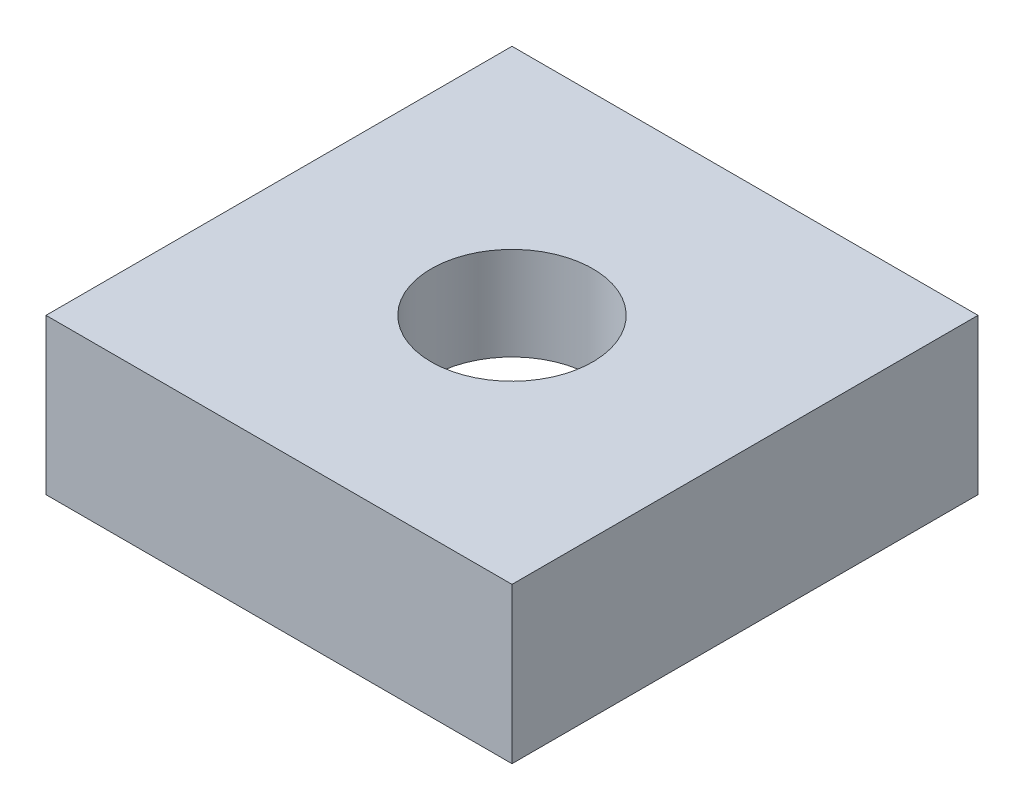
SolidWorks part; units mm, degrees
ref_plane "Alzado" through (0, 0, 0) normal (0, 0, 1) x (1, 0, 0)
ref_plane "Planta" through (0, 0, 0) normal (0, 1, 0) x (1, 0, 0)
ref_plane "Vista lateral" through (0, 0, 0) normal (1, 0, 0) x (0, 0, -1)
sketch "Croquis1" plane through (0, 0, 0) normal (0, 1, 0) x (1, 0, 0)
  line L1 (0, 0) -> (15, 0)
  line L2 (0, 0) -> (0, 15)
  line L3 (0, 15) -> (15, 15)
  line L4 (15, 0) -> (15, 15)
  dimension "D1" = 15
extrude "Saliente-Extruir1" add sketch "Croquis1" along normal blind 5
sketch "Croquis2" plane through (0, 5, 0) normal (0, 1, 0) x (1, 0, 0)
  line L0 (0, 0) -> (15, 15) construction
  circle A0 centre (7.5, 7.5) radius 2.6
  dimension "D1" = 5.2
extrude "Cortar-Extruir1" cut sketch "Croquis2" against normal blind 5
sketch "Croquis3" plane through (0, 0, 0) normal (0, -1, 0) x (1, 0, 0)
  line L1 (0, -15) -> (12.5, -15)
  line L2 (0, -15) -> (0, -2.5)
  line L3 (0, -2.5) -> (12.5, -2.5)
  line L4 (12.5, -15) -> (12.5, -2.5)
  circle A0 centre (7.5, -7.5) radius 2.6 construction
  dimension "D1" = 5
extrude "Cortar-Extruir2" cut sketch "Croquis3" against normal blind 2
